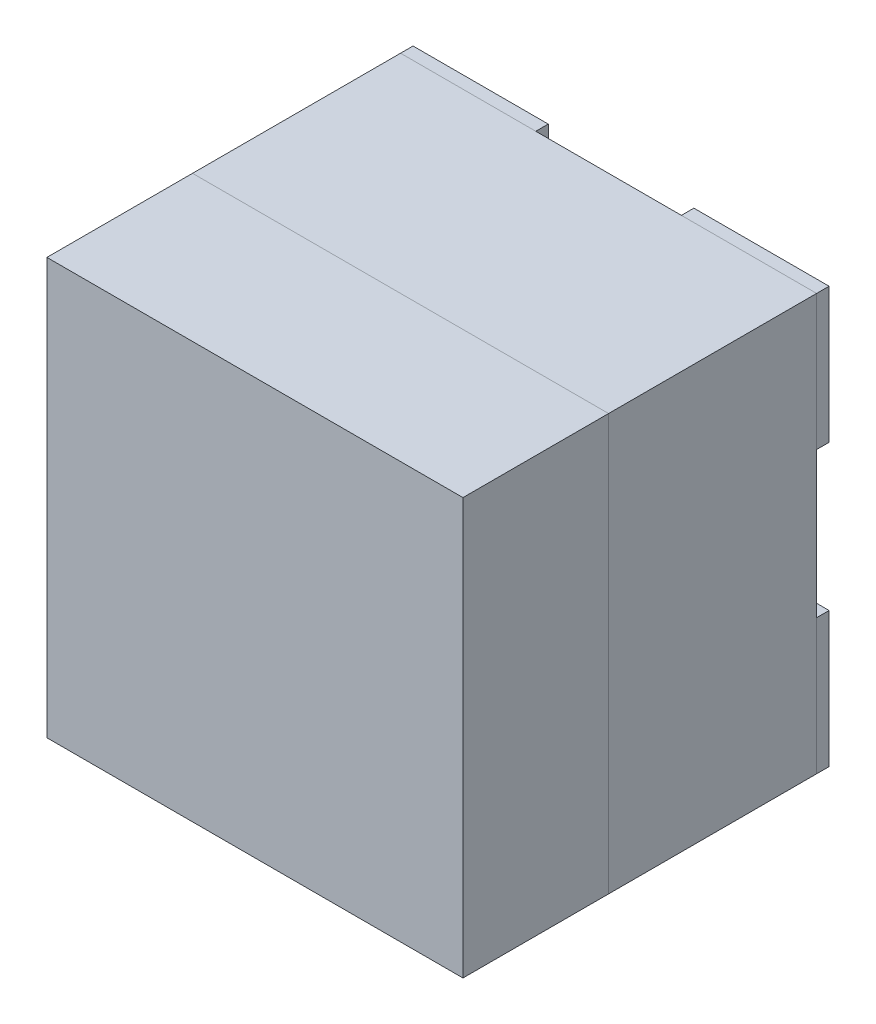
SolidWorks part; units mm, degrees
ref_plane "Ebene vorne" through (0, 0, 0) normal (0, 0, 1) x (1, 0, 0)
ref_plane "Ebene oben" through (0, 0, 0) normal (0, 1, 0) x (1, 0, 0)
ref_plane "Ebene rechts" through (0, 0, 0) normal (1, 0, 0) x (0, 0, -1)
sketch "Skizze1" plane through (0, 0, 0) normal (0, 0, 1) x (1, 0, 0)
  line L1 (-0.5, 0.5) -> (0.5, 0.5)
  line L2 (-0.5, 0.5) -> (-0.5, -0.5)
  line L3 (-0.5, -0.5) -> (0.5, -0.5)
  line L4 (0.5, 0.5) -> (0.5, -0.5)
  line L5 (-0.5, 0.5) -> (0.5, -0.5) construction
  line L6 (-0.5, -0.5) -> (0.5, 0.5) construction
  point P0 (0, 0)
  dimension "D1" = 1
  dimension "D2" = 1
extrude "Aufsatz-Linear austragen1" add sketch "Skizze1" along normal blind 0.5
sketch "Skizze2" plane through (0, 0, 0) normal (0, 0, -1) x (-1, 0, 0)
  line L1 (-0.175, 0.175) -> (0.175, 0.175) construction
  line L2 (-0.175, 0.175) -> (-0.175, -0.175) construction
  line L3 (-0.175, -0.175) -> (0.175, -0.175) construction
  line L4 (0.175, 0.175) -> (0.175, -0.175) construction
  line L5 (-0.175, 0.175) -> (0.175, -0.175) construction
  line L6 (-0.175, -0.175) -> (0.175, 0.175) construction
  line L7 (-0.5, 0.5) -> (-0.175, 0.5)
  line L8 (-0.5, 0.5) -> (-0.5, 0.175)
  line L9 (-0.5, 0.175) -> (-0.175, 0.175)
  line L10 (-0.175, 0.5) -> (-0.175, 0.175)
  line L11 (0.5, 0.5) -> (0.175, 0.5)
  line L12 (0.5, 0.5) -> (0.5, 0.175)
  line L13 (0.5, 0.175) -> (0.175, 0.175)
  line L14 (0.175, 0.5) -> (0.175, 0.175)
  line L15 (-0.5, -0.5) -> (-0.175, -0.5)
  line L16 (-0.5, -0.5) -> (-0.5, -0.175)
  line L17 (-0.5, -0.175) -> (-0.175, -0.175)
  line L18 (-0.175, -0.5) -> (-0.175, -0.175)
  line L19 (0.5, -0.5) -> (0.175, -0.5)
  line L20 (0.5, -0.5) -> (0.5, -0.175)
  line L21 (0.5, -0.175) -> (0.175, -0.175)
  line L22 (0.175, -0.5) -> (0.175, -0.175)
  point P0 (0, 0)
  point P22 (0, 0)
  dimension "D1" = 0.35
  dimension "D2" = 0.35
extrude "Aufsatz-Linear austragen2" add sketch "Skizze2" along normal blind 0.03 separate body
sketch "Skizze3" plane through (0, 0, 0.5) normal (0, 0, 1) x (1, 0, 0)
  line L1 (-0.5, 0.5) -> (0.5, 0.5)
  line L2 (-0.5, 0.5) -> (-0.5, -0.5)
  line L3 (-0.5, -0.5) -> (0.5, -0.5)
  line L4 (0.5, 0.5) -> (0.5, -0.5)
extrude "Aufsatz-Linear austragen3" add sketch "Skizze3" along normal blind 0.35 separate body
